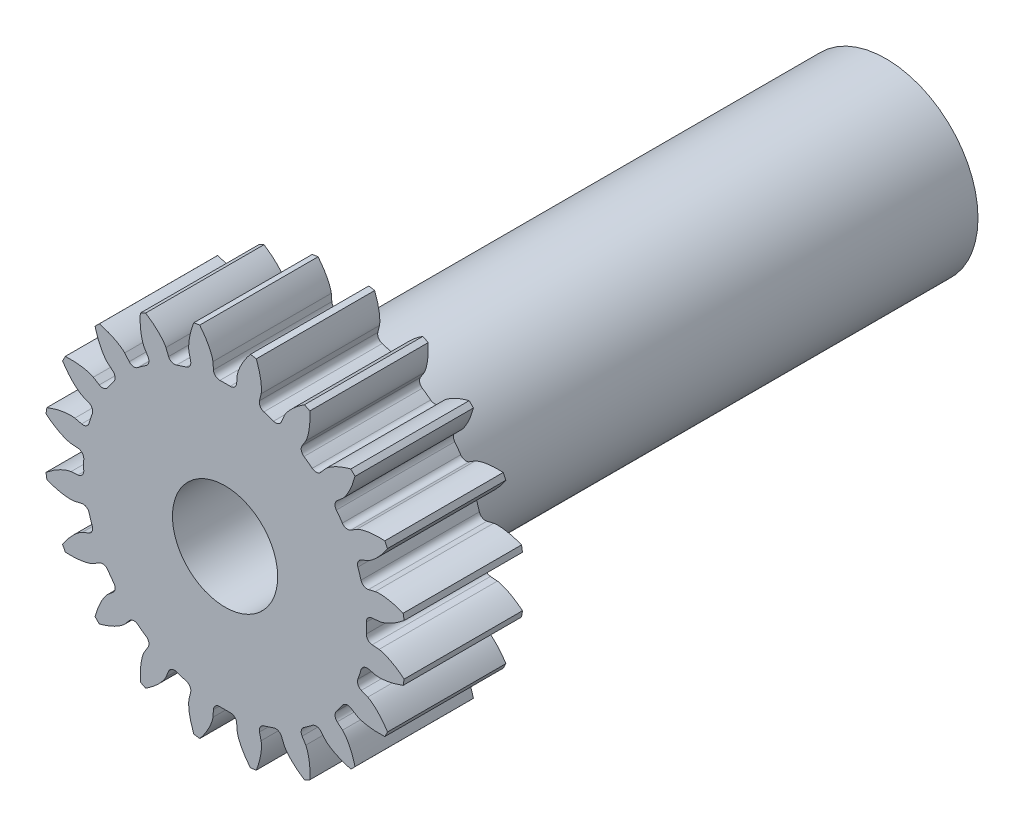
SolidWorks part; units mm, degrees
ref_plane "Front Plane" through (0, 0, 0) normal (0, 0, 1) x (1, 0, 0)
ref_plane "Top Plane" through (0, 0, 0) normal (0, 1, 0) x (1, 0, 0)
ref_plane "Right Plane" through (0, 0, 0) normal (1, 0, 0) x (0, 0, -1)
ref_axis "Gear Axis" through (0, 0, -0.2501) along (0, 0, 1)
sketch "Blank Sketch" plane through (0, 0, 0) normal (0, 0, 1) x (1, 0, 0)
  circle A0 centre (0, 0) radius 13.75
  dimension "OD" = 27.5
extrude "Blank" add sketch "Blank Sketch" along normal blind 9
sketch "Tooth Space Sketch" plane through (0, 0, 0) normal (0, 0, 1) x (1, 0, 0)
  line L0 (11.7099, 0.9227) -> (11.1803, 0.881)
  line L1 (11.7099, -0.9227) -> (11.1803, -0.881)
  line L2 (14.6961, 3.0042) -> (14.6961, -3.0042)
  arc A0 (11.1803, 0.881) -> (10.7429, 0.3902) centre (11.2176, 0.4075) ccw
  arc A1 (10.7429, -0.3902) -> (11.1803, -0.881) centre (11.2176, -0.4075) ccw
  arc A2 (10.7429, -0.3902) -> (10.7429, 0.3902) centre (0, 0) ccw
  spline S0 degree 4 poles (11.7099, 0.9227) (11.7153, 0.9232) (11.7306, 0.925) (11.7593, 0.9294) (11.806, 0.9382) (11.8651, 0.9517) (11.9409, 0.9719) (12.0295, 0.999) (12.1261, 1.0323) (12.2301, 1.0723) (12.3329, 1.1155) (12.4344, 1.1617) (12.5347, 1.2105) (12.6549, 1.2727) (12.7975, 1.3519) (12.9615, 1.4507) (13.1443, 1.5703) (13.3269, 1.7) (13.5034, 1.834) (13.678, 1.9766) (13.8441, 2.1196) (14.0125, 2.2754) (14.1658, 2.4228) (14.3326, 2.5956) (14.4659, 2.7374) (14.6362, 2.9324) (14.7351, 3.0499) (14.8489, 3.1902) (14.8984, 3.2539) (14.9289, 3.293) knots 0 0 0 0 0 0.005377 0.015084 0.028532 0.04661 0.064855 0.092111 0.119476 0.146842 0.174209 0.201575 0.228941 0.256307 0.307035 0.361767 0.4165 0.471232 0.525964 0.580697 0.635429 0.690161 0.744894 0.799626 0.854358 0.909091 0.954545 1 1 1 1 1 construction
  spline S1 degree 4 poles (11.7099, 0.9227) (11.7153, 0.9232) (11.7306, 0.925) (11.7593, 0.9294) (11.806, 0.9382) (11.8651, 0.9517) (11.9409, 0.9719) (12.0295, 0.999) (12.1261, 1.0323) (12.2301, 1.0723) (12.3329, 1.1155) (12.4344, 1.1617) (12.5347, 1.2105) (12.6549, 1.2727) (12.7975, 1.3519) (12.9615, 1.4507) (13.1443, 1.5703) (13.3269, 1.7) (13.5034, 1.834) (13.678, 1.9766) (13.8441, 2.1196) (14.0125, 2.2754) (14.1658, 2.4228) (14.3326, 2.5956) (14.4659, 2.7374) (14.5992, 2.8901) (14.6635, 2.9654) (14.6961, 3.0042) knots 0 0 0 0 0 0.005377 0.015084 0.028532 0.04661 0.064855 0.092111 0.119476 0.146842 0.174209 0.201575 0.228941 0.256307 0.307035 0.361767 0.4165 0.471232 0.525964 0.580697 0.635429 0.690161 0.744894 0.799626 0.854358 0.909091 0.909091 0.909091 0.909091 0.909091
  spline S2 degree 4 poles (11.7099, -0.9227) (11.7153, -0.9232) (11.7306, -0.925) (11.7593, -0.9294) (11.806, -0.9382) (11.8651, -0.9517) (11.9409, -0.9719) (12.0295, -0.999) (12.1261, -1.0323) (12.2301, -1.0723) (12.3329, -1.1155) (12.4344, -1.1617) (12.5347, -1.2105) (12.6549, -1.2727) (12.7975, -1.3519) (12.9615, -1.4507) (13.1443, -1.5703) (13.3269, -1.7) (13.5034, -1.834) (13.678, -1.9766) (13.8441, -2.1196) (14.0125, -2.2754) (14.1658, -2.4228) (14.3326, -2.5956) (14.4659, -2.7374) (14.6362, -2.9324) (14.7351, -3.0499) (14.8489, -3.1902) (14.8984, -3.2539) (14.9289, -3.293) knots 0 0 0 0 0 0.005377 0.015084 0.028532 0.04661 0.064855 0.092111 0.119476 0.146842 0.174209 0.201575 0.228941 0.256307 0.307035 0.361767 0.4165 0.471232 0.525964 0.580697 0.635429 0.690161 0.744894 0.799626 0.854358 0.909091 0.954545 1 1 1 1 1 construction
  spline S3 degree 4 poles (11.7099, -0.9227) (11.7153, -0.9232) (11.7306, -0.925) (11.7593, -0.9294) (11.806, -0.9382) (11.8651, -0.9517) (11.9409, -0.9719) (12.0295, -0.999) (12.1261, -1.0323) (12.2301, -1.0723) (12.3329, -1.1155) (12.4344, -1.1617) (12.5347, -1.2105) (12.6549, -1.2727) (12.7975, -1.3519) (12.9615, -1.4507) (13.1443, -1.5703) (13.3269, -1.7) (13.5034, -1.834) (13.678, -1.9766) (13.8441, -2.1196) (14.0125, -2.2754) (14.1658, -2.4228) (14.3326, -2.5956) (14.4659, -2.7374) (14.5992, -2.8901) (14.6635, -2.9654) (14.6961, -3.0042) knots 0 0 0 0 0 0.005377 0.015084 0.028532 0.04661 0.064855 0.092111 0.119476 0.146842 0.174209 0.201575 0.228941 0.256307 0.307035 0.361767 0.4165 0.471232 0.525964 0.580697 0.635429 0.690161 0.744894 0.799626 0.854358 0.909091 0.909091 0.909091 0.909091 0.909091
  dimension "Root" = 10.75
  dimension "Fillet" = 0.475
extrude "Tooth Space" cut sketch "Tooth Space Sketch" against normal through all both and the other way through all both
pattern_circular "Teeth" count 20 over 360 about axis through (0, 0, -0.2501) along (0, 0, 1) of "Tooth Space"
sketch "Bore Sketch" plane through (0, 0, 0) normal (0, 0, 1) x (1, 0, 0)
  circle A0 centre (0, 0) radius 7
  dimension "Bore" = 14
extrude "Bore" cut sketch "Bore Sketch" against normal through all both and the other way through all both
sketch "Sketch1" plane through (0, 0, 9) normal (0, 0, 1) x (1, 0, 0)
  circle A0 centre (0, 0) radius 7 construction
  circle A1 centre (0, 0) radius 7
  circle A2 centre (0, 0) radius 4 construction
  circle A3 centre (0, 0) radius 4
extrude "Boss-Extrude1" add sketch "Sketch1" against normal blind 50.25
equation "\"No. of Teeth\"= 20"
equation "\"Module\"= 1.25"
equation "\"Bore Diameter\"= 14"
equation "\"Pressure Angle\"= 20"
equation "\"Outer Diameter\"= ( \"No. of Teeth\" + 2 ) * \"Module\""
equation "\"Pitch Diameter\"= \"No. of Teeth\" * \"Module\""
equation "\"Backlash\"= 0.3 * \"Module\""
equation "\"Arc Length\"= ( ( \"Module\" * pi ) / 2 + \"Backlash\" )"
equation "\"Fillet Radius\"= 0.38 * \"Module\""
equation "\"Tooth Depth\"= IIF ( \"Module\" <= 1.25 , \"Module\" * 2.4 , \"Module\" * 2.25 )"
equation "\"Face Width\"= 9"
equation "\"Root Diameter\"= \"Outer Diameter\" - 2 * \"Tooth Depth\""
equation "\"Base Diameter\"= \"Pitch Diameter\" * cos ( \"Pressure Angle\" )"
equation "\"Base Radius\"= \"Base Diameter\" / 2"
equation "\"Tooth Thickness\"= \"Module\" * pi - \"Arc Length\""
equation "\"Half Space Angle\"= ( \"Arc Length\" / \"Pitch Diameter\" ) * 180 / pi"
equation "\"Involute Fn\"= tan ( \"Pressure Angle\" ) - \"Pressure Angle\" * pi / 180"
equation "\"Flank Offset\"= \"Arc Length\" / \"Pitch Diameter\" - \"Involute Fn\""
equation "\"Tip Cap Diameter\"= \"Outer Diameter\" + 2 * \"Module\""
equation "\"Flank Start Diameter\"= IIF ( \"Base Diameter\" >= ( \"Root Diameter\" + 3 * \"Fillet Radius\" ) , \"Base Diameter\" , \"Root Diameter\" + 3 * \"Fillet Radius\" )"
equation "\"Involute t1\"= ( abs ( ( \"Flank Start Diameter\" / \"Base Diameter\" ) ^ 2 - 1 ) ) ^ 0.5"
equation "\"Involute t2\"= ( abs ( ( \"Tip Cap Diameter\" / \"Base Diameter\" ) ^ 2 - 1 ) ) ^ 0.5"
equation "\"Flank Arc Radius\"= ( \"Pitch Diameter\" / 2 ) * sin ( \"Pressure Angle\" )"
equation "\"Flank Centre Angle\"= \"Half Space Angle\" + \"Pressure Angle\""
equation "\"OD@Blank Sketch\"= \"Outer Diameter\""
equation "\"Width@Blank\"= \"Face Width\""
equation "\"Root@Tooth Space Sketch\"= \"Root Diameter\" / 2"
equation "\"Fillet@Tooth Space Sketch\"= \"Fillet Radius\""
equation "\"Count@Teeth\"= \"No. of Teeth\""
equation "\"Bore@Bore Sketch\"= \"Bore Diameter\""
